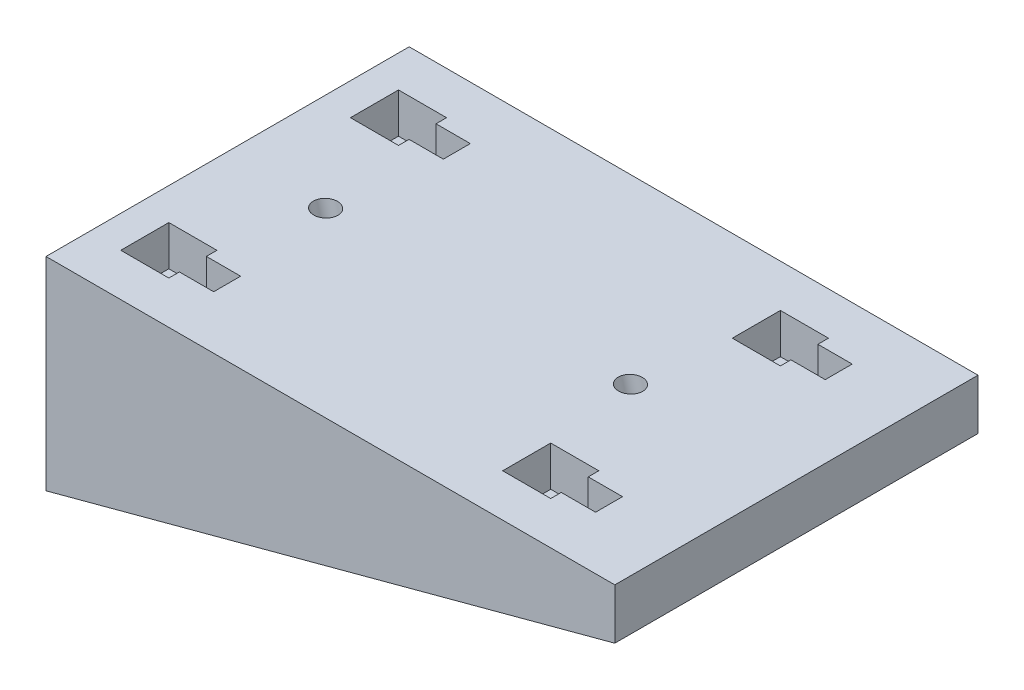
SolidWorks part; units mm, degrees
ref_plane "Front Plane" through (0, 0, 0) normal (0, 0, 1) x (1, 0, 0)
ref_plane "Top Plane" through (0, 0, 0) normal (0, 1, 0) x (1, 0, 0)
ref_plane "Right Plane" through (0, 0, 0) normal (1, 0, 0) x (0, 0, -1)
other "Bounding Box"
ref_plane "Default Plane" through (-106.5, -54, 68) normal (0, 0, -1) x (-1, 0, 0)
sketch "Sketch1" plane through (0, 0, 0) normal (0, 1, 0) x (1, 0, 0)
  line L1 (-106.5, -68) -> (106.5, -68)
  line L2 (-106.5, -68) -> (-106.5, 68)
  line L3 (-106.5, 68) -> (106.5, 68)
  line L4 (106.5, -68) -> (106.5, 68)
  line L5 (-106.5, -68) -> (106.5, 68) construction
  line L6 (-106.5, 68) -> (106.5, -68) construction
  point P0 (0, 0)
  dimension "D1" = 136
  dimension "D2" = 213
extrude "Boss-Extrude1" add sketch "Sketch1" along normal blind 22 and the other way blind 54 contours L2 L1 L4 L3
sketch "Sketch2" plane through (0, 22, 0) normal (0, 1, 0) x (1, 0, 0)
  line L0 (-106.5, 68) -> (106.5, 68) construction
  line L1 (-94.5, 52) -> (-76.5, 52)
  line L2 (-94.5, 52) -> (-94.5, 34)
  line L3 (-94.5, 34) -> (-76.5, 34)
  line L4 (-76.5, 52) -> (-76.5, 34)
  line L5 (-94.5, 52) -> (-76.5, 34) construction
  line L6 (-94.5, 34) -> (-76.5, 52) construction
  line L7 (-106.5, -68) -> (-106.5, 68) construction
  line L12 (-106.5, -68) -> (106.5, -68) construction
  line L13 (-94.5, -52) -> (-76.5, -52)
  line L14 (-94.5, -52) -> (-94.5, -34)
  line L15 (-94.5, -34) -> (-76.5, -34)
  line L16 (-76.5, -52) -> (-76.5, -34)
  line L17 (-94.5, -52) -> (-76.5, -34) construction
  line L18 (-94.5, -34) -> (-76.5, -52) construction
  line L19 (48.5, 52) -> (66.5, 52)
  line L20 (48.5, 52) -> (48.5, 34)
  line L21 (48.5, 34) -> (66.5, 34)
  line L22 (66.5, 52) -> (66.5, 34)
  line L23 (48.5, 52) -> (66.5, 34) construction
  line L24 (48.5, 34) -> (66.5, 52) construction
  line L25 (48.5, -52) -> (66.5, -52)
  line L26 (48.5, -52) -> (48.5, -34)
  line L27 (48.5, -34) -> (66.5, -34)
  line L28 (66.5, -52) -> (66.5, -34)
  line L29 (48.5, -52) -> (66.5, -34) construction
  line L30 (48.5, -34) -> (66.5, -52) construction
  line L31 (106.5, -68) -> (106.5, 68) construction
  point P0 (-85.5, 43)
  point P9 (-85.5, -43)
  point P16 (57.5, 43)
  point P21 (57.5, -43)
  dimension "D1" = 18
  dimension "D2" = 18
  dimension "D3" = 25
  dimension "D4" = 21
  dimension "D5" = 25
  dimension "D6" = 21
  dimension "D7" = 18
  dimension "D8" = 18
  dimension "D9" = 18
  dimension "D10" = 18
  dimension "D11" = 18
  dimension "D12" = 18
  dimension "D13" = 25
  dimension "D14" = 49
  dimension "D15" = 49
  dimension "D16" = 25
extrude "Cut-Extrude1" cut sketch "Sketch2" against normal blind 15
sketch "Sketch4" plane through (-76.5, 0, 0) normal (-1, 0, 0) x (0, 0, 1)
  line L0 (52, 7) -> (52, 22) construction
  line L1 (34, 7) -> (52, 7)
  line L2 (34, 7) -> (34, 11)
  line L3 (34, 11) -> (37.95, 11)
  line L4 (52, 7) -> (52, 11)
  line L5 (34, 7) -> (52, 11) construction
  line L6 (34, 11) -> (52, 7) construction
  line L7 (48.05, 11) -> (52, 11)
  line L8 (34, 7) -> (34, 22) construction
  line L9 (52, 7) -> (34, 7) construction
  line L10 (-34, 7) -> (-52, 7)
  line L11 (37.95, 24.1948) -> (48.05, 24.1948)
  line L12 (37.95, 24.1948) -> (37.95, 11)
  line L14 (48.05, 24.1948) -> (48.05, 11)
  line L15 (37.95, 24.1948) -> (48.05, 11) construction
  line L16 (37.95, 11) -> (48.05, 24.1948) construction
  line L17 (-34, 7) -> (-34, 11)
  line L18 (-34, 11) -> (-37.95, 11)
  line L19 (-52, 7) -> (-52, 11)
  line L20 (-34, 7) -> (-52, 11) construction
  line L21 (-34, 11) -> (-52, 7) construction
  line L22 (-48.05, 24.1948) -> (-37.95, 24.1948)
  line L23 (-48.05, 24.1948) -> (-48.05, 11)
  line L25 (-37.95, 24.1948) -> (-37.95, 11)
  line L26 (-48.05, 24.1948) -> (-37.95, 11) construction
  line L27 (-48.05, 11) -> (-37.95, 24.1948) construction
  line L28 (-34, 7) -> (-52, 7) construction
  line L29 (-48.05, 11) -> (-52, 11)
  point P0 (43, 9)
  point P11 (43, 17.5974)
  point P17 (-43, 9)
  point P22 (-43, 17.5974)
  point P29 (-43, 7)
  point P30 (-43, 7)
  dimension "D1" = 4
  dimension "D2" = 10.1
  dimension "D3" = 10.1
  dimension "D4" = 18
extrude "Cut-Extrude2" cut sketch "Sketch4" against normal blind 12.84
sketch "Sketch5" plane through (66.5, 0, 0) normal (-1, 0, 0) x (0, 0, 1)
  line L0 (34, 7) -> (52, 7)
  line L1 (34, 7) -> (34, 11)
  line L2 (34, 11) -> (37.95, 11)
  line L3 (52, 7) -> (52, 11)
  line L4 (34, 7) -> (52, 11) construction
  line L5 (34, 11) -> (52, 7) construction
  line L6 (48.05, 11) -> (52, 11)
  line L7 (-34, 7) -> (-52, 7)
  line L8 (37.95, 24.1948) -> (48.05, 24.1948)
  line L9 (37.95, 24.1948) -> (37.95, 11)
  line L10 (48.05, 24.1948) -> (48.05, 11)
  line L11 (37.95, 24.1948) -> (48.05, 11) construction
  line L12 (37.95, 11) -> (48.05, 24.1948) construction
  line L13 (-34, 7) -> (-34, 11)
  line L14 (-34, 11) -> (-37.95, 11)
  line L15 (-52, 7) -> (-52, 11)
  line L16 (-34, 7) -> (-52, 11) construction
  line L17 (-34, 11) -> (-52, 7) construction
  line L18 (-48.05, 24.1948) -> (-37.95, 24.1948)
  line L19 (-48.05, 24.1948) -> (-48.05, 11)
  line L20 (-37.95, 24.1948) -> (-37.95, 11)
  line L21 (-48.05, 24.1948) -> (-37.95, 11) construction
  line L22 (-48.05, 11) -> (-37.95, 24.1948) construction
  line L23 (-48.05, 11) -> (-52, 11)
  line L24 (-34, 7) -> (-52, 7) construction
  line L25 (52, 7) -> (34, 7) construction
  line L26 (52, 7) -> (52, 22) construction
  line L27 (34, 7) -> (34, 22) construction
  point P0 (43, 9)
  point P5 (43, 17.5974)
  point P10 (-43, 9)
  point P15 (-43, 17.5974)
  point P20 (-43, 7)
  point P23 (-43, 7)
  dimension "D1" = 4
  dimension "D2" = 10.1
  dimension "D3" = 10.1
  dimension "D4" = 18
  dimension "D5" = 4
extrude "Cut-Extrude3" cut sketch "Sketch5" against normal blind 12.84
sketch "Sketch6" plane through (0, -54, 0) normal (0, -1, 0) x (1, 0, 0)
sketch "Sketch7" plane through (0, 0, -68) normal (0, 0, -1) x (-1, 0, 0)
  line L0 (106.5, -54) -> (-106.5, 3.0732)
  line L4 (106.5, -54) -> (-106.5, -54) construction
  line L5 (-106.5, 3.0732) -> (-106.5, -54)
  line L7 (-106.5, -54) -> (-106.5, 22) construction
  line L8 (-106.5, -54) -> (106.5, -54)
  dimension "D1" = 15
extrude "Cut-Extrude4" cut sketch "Sketch7" against normal through all
sketch "Sketch9" plane through (6.3659, -23.7577, 0) normal (0.2588, -0.9659, 0) x (0.9659, 0.2588, 0)
  line L0 (-116.8473, 68) -> (-116.8473, -68) construction
  line L1 (-116.8473, -68) -> (103.6665, -68) construction
  line L2 (103.6665, 68) -> (103.6665, -68) construction
  circle A0 centre (-61.7198, 0) radius 1.905
  circle A1 centre (48.539, 0) radius 1.905
  dimension "D1" = 3.81
  dimension "D2" = 3.81
  dimension "D3" = 55.1275
  dimension "D4" = 68
  dimension "D5" = 68
  dimension "D6" = 55.1275
extrude "Cut-Extrude8" cut sketch "Sketch9" against normal blind 5
sketch "Sketch11" plane through (5.0718, -18.9281, 0) normal (0.2588, -0.9659, 0) x (0.9659, 0.2588, 0)
  circle A0 centre (-61.7198, 0) radius 4.445
  circle A1 centre (48.539, 0) radius 4.445
  circle A2 centre (-61.7198, 0) radius 1.905 construction
  circle A3 centre (48.539, 0) radius 1.905 construction
  dimension "D1" = 8.89
  dimension "D2" = 8.89
extrude "Cut-Extrude10" cut sketch "Sketch11" against normal through all
